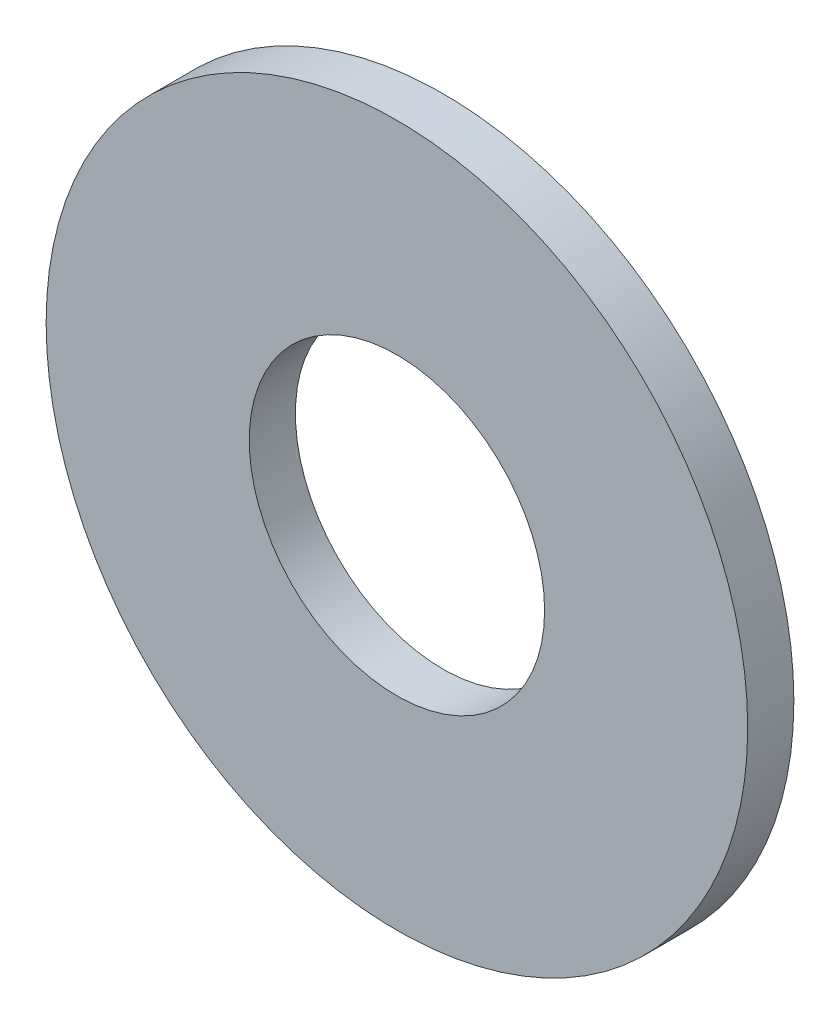
SolidWorks part; units mm, degrees
ref_plane "Front Plane" through (0, 0, 0) normal (0, 0, 1) x (1, 0, 0)
ref_plane "Top Plane" through (0, 0, 0) normal (0, 1, 0) x (1, 0, 0)
ref_plane "Right Plane" through (0, 0, 0) normal (1, 0, 0) x (0, 0, -1)
sketch "Sketch1" plane through (0, 0, 0) normal (0, 0, 1) x (1, 0, 0)
  circle A0 centre (2558.0825, 2698.6868) radius 4.826
  circle A1 centre (2558.0825, 2698.6868) radius 2.032
extrude "Boss-Extrude1" add sketch "Sketch1" along normal blind 0.635
